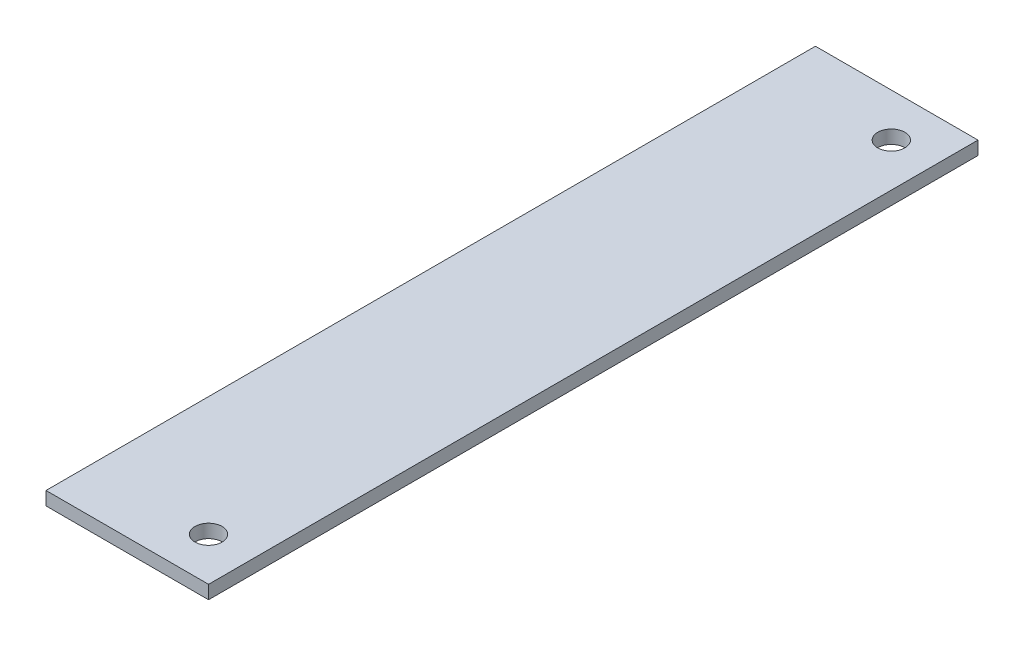
SolidWorks part; units mm, degrees
material "E-Glass Fiber"
ref_plane "Front Plane" through (0, 0, 0) normal (0, 0, 1) x (1, 0, 0)
ref_plane "Top Plane" through (0, 0, 0) normal (0, 1, 0) x (1, 0, 0)
ref_plane "Right Plane" through (0, 0, 0) normal (1, 0, 0) x (0, 0, -1)
sketch "Sketch1" plane through (0, 0, 0) normal (0, 1, 0) x (1, 0, 0)
  line L1 (-9.525, -45.085) -> (9.525, -45.085)
  line L2 (-9.525, -45.085) -> (-9.525, 45.085)
  line L3 (-9.525, 45.085) -> (9.525, 45.085)
  line L4 (9.525, -45.085) -> (9.525, 45.085)
  line L5 (-9.525, -45.085) -> (9.525, 45.085) construction
  line L6 (-9.525, 45.085) -> (9.525, -45.085) construction
  point P0 (0, 0)
  dimension "D1" = 90.17
  dimension "D2" = 19.05
extrude "Boss-Extrude1" add sketch "Sketch1" along normal blind 1.57
sketch "Sketch2" plane through (0, 1.57, 0) normal (0, 1, 0) x (1, 0, 0)
  line L0 (9.525, -45.085) -> (9.525, 45.085) construction
  line L1 (-9.525, -45.085) -> (9.525, -45.085) construction
  circle A0 centre (4.445, -40.005) radius 1.59
  circle A1 centre (4.445, 40.005) radius 1.59
  dimension "D3" = 3.18
  dimension "D4" = 3.18
  dimension "D1" = 5.08
  dimension "D2" = 5.08
  dimension "D5" = 5.08
  dimension "D6" = 80.01
extrude "Cut-Extrude1" cut sketch "Sketch2" against normal through all
